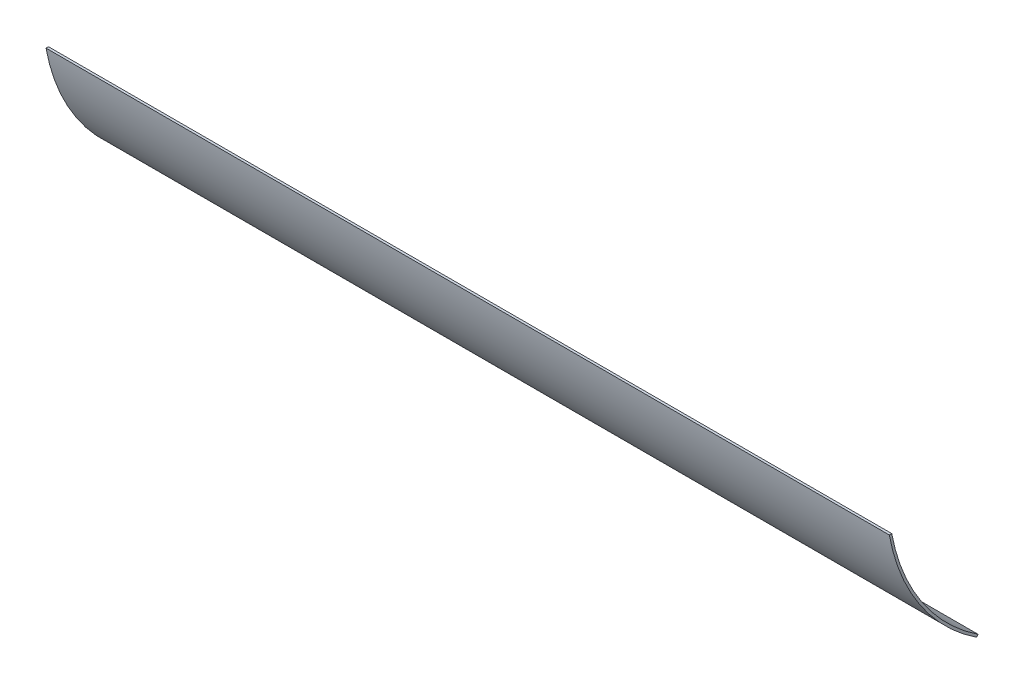
SolidWorks part; units mm, degrees
material "Acrylic (Medium-high impact)"
ref_plane "Front Plane" through (0, 0, 0) normal (0, 0, 1) x (1, 0, 0)
ref_plane "Top Plane" through (0, 0, 0) normal (0, 1, 0) x (1, 0, 0)
ref_plane "Right Plane" through (0, 0, 0) normal (1, 0, 0) x (0, 0, -1)
sketch "Sketch1" plane through (0, 0, 0) normal (1, 0, 0) x (0, 0, -1)
  line L1 (-129.9041, -23.876) -> (-131.5178, -23.876)
  line L2 (-72.7541, -110.236) -> (-73.6285, -111.5609)
  arc A0 (-129.9041, -23.876) -> (-72.7541, -110.236) centre (0, 0) ccw
  arc A1 (-131.5178, -23.876) -> (-73.6285, -111.5609) centre (0, 0) ccw
  dimension "D1" = 132.08
  dimension "D2" = 1.5875
  dimension "D3" = 57.15
  dimension "D4" = 23.876
extrude "Boss-Extrude1" add sketch "Sketch1" along normal blind 558.8
